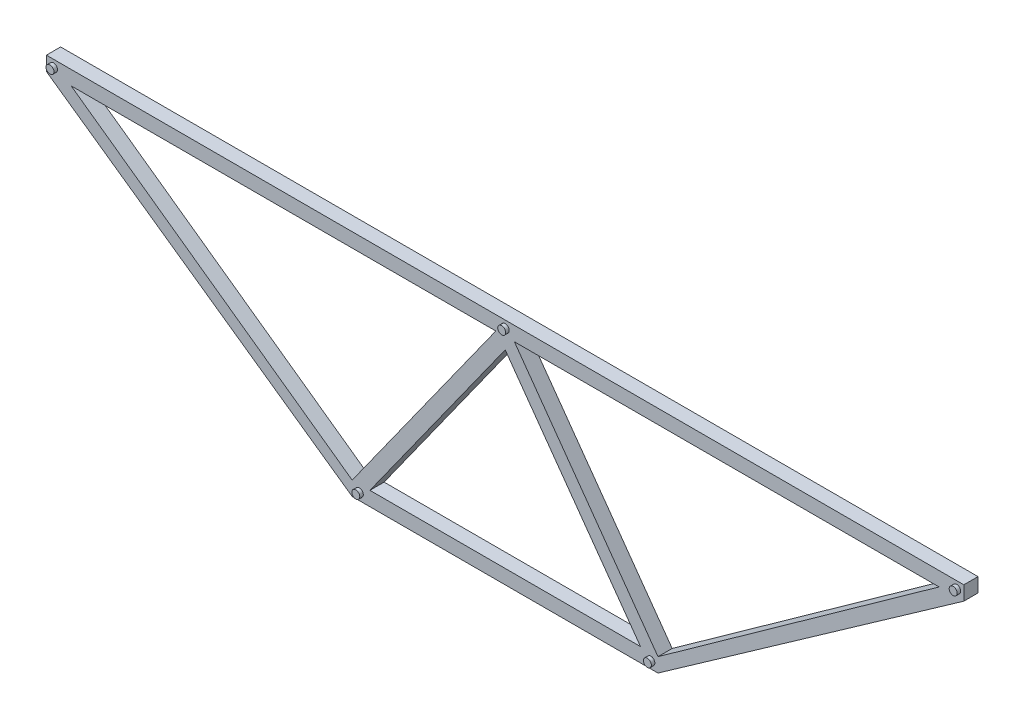
SolidWorks part; units mm, degrees
material "A 500 STEEL"
ref_plane "Front Plane" through (0, 0, 0) normal (0, 0, 1) x (1, 0, 0)
ref_plane "Top Plane" through (0, 0, 0) normal (0, 1, 0) x (1, 0, 0)
ref_plane "Right Plane" through (0, 0, 0) normal (1, 0, 0) x (0, 0, -1)
sketch "Sketch2" plane through (0, 0, 0) normal (0, 0, 1) x (1, 0, 0)
  line L0 (0, 0) -> (1200, 0)
  line L1 (0, 0) -> (0, -18.59)
  line L2 (0, -18.59) -> (400, -300)
  line L3 (400, -300) -> (800, -300)
  line L4 (800, -300) -> (1200, -18.59)
  line L5 (1200, -18.59) -> (1200, 0)
  dimension "D1" = 1200
  dimension "D2" = 18.59
  dimension "D3" = 300
  dimension "D4" = 400
extrude "Boss-Extrude1" add sketch "Sketch2" along normal blind 18.59
sketch "Sketch3" plane through (0, 0, 18.59) normal (0, 0, 1) x (1, 0, 0)
  line L0 (32.3082, 0) -> (32.3082, -18.59) construction
  line L1 (1200, 0) -> (0, 0) construction
  line L2 (21.6116, -33.7943) -> (32.3082, -18.59) construction
  line L3 (0, -18.59) -> (400, -300) construction
  line L6 (400, -300) -> (400, -281.41) construction
  line L7 (32.3082, -18.59) -> (400, -281.41)
  line L8 (400, -281.41) -> (587.8594, -18.59)
  line L9 (587.8594, -18.59) -> (32.3082, -18.59)
  line L12 (556.1658, -62.9301) -> (571.2896, -73.7403) construction
  line L13 (600.1563, -33.7923) -> (423.1633, -281.41)
  line L14 (800, -300) -> (800, -281.41) construction
  line L15 (1178.3884, -33.7943) -> (1167.6918, -18.59) construction
  line L16 (800, -300) -> (1200, -18.59) construction
  line L17 (800, -281.41) -> (1167.6918, -18.59)
  line L18 (633.8432, -48.9525) -> (618.7195, -59.7627) construction
  line L19 (800, -281.41) -> (612.1406, -18.59)
  line L20 (612.1406, -18.59) -> (1167.6918, -18.59)
  line L21 (671.7379, -281.41) -> (671.7379, -300) construction
  line L22 (777.1493, -281.41) -> (423.1633, -281.41)
  line L23 (767.4609, 0) -> (767.4609, -18.59) construction
  line L24 (400, -300) -> (800, -300) construction
  line L25 (777.1493, -281.41) -> (600.1563, -33.7923)
  dimension "D1" = 18.59
  dimension "D2" = 18.59
  dimension "D3" = 18.59
  dimension "D4" = 18.59
  dimension "D5" = 18.59
  dimension "D6" = 18.59
  dimension "D7" = 18.59
  dimension "D8" = 18.59
  dimension "D9" = 18.59
extrude "Cut-Extrude2" cut sketch "Sketch3" against normal through all
sketch "Sketch4" plane through (0, 0, 0) normal (0, 0, -1) x (-1, 0, 0)
  line L0 (-1200, 0) -> (0, 0) construction
  line L1 (-1200, -18.59) -> (-1200, 0) construction
  line L2 (0, 0) -> (0, -18.59) construction
  line L3 (-400, -300) -> (-800, -300) construction
  circle A0 centre (-1190.705, -9.295) radius 5.207
  circle A1 centre (-600.1563, -9.295) radius 5.207
  circle A2 centre (-9.295, -9.295) radius 5.207
  circle A3 centre (-790.705, -290.705) radius 5.207
  circle A4 centre (-409.295, -290.705) radius 5.207
  dimension "D3" = 10.414
  dimension "D4" = 9.295
  dimension "D1" = 9.295
  dimension "D2" = 9.295
  dimension "D5" = 9.295
  dimension "D6" = 9.295
  dimension "D7" = 9.295
extrude "Boss-Extrude3" add sketch "Sketch4" against normal blind 23.2
